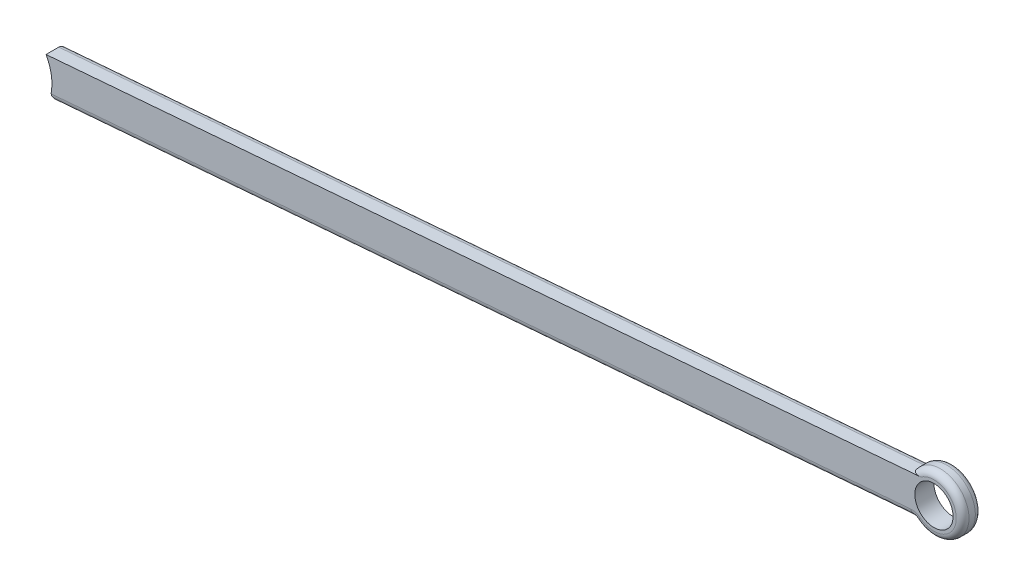
SolidWorks part; units mm, degrees
ref_plane "Front Plane" through (0, 0, 0) normal (0, 0, 1) x (1, 0, 0)
ref_plane "Top Plane" through (0, 0, 0) normal (0, 1, 0) x (1, 0, 0)
ref_plane "Right Plane" through (0, 0, 0) normal (1, 0, 0) x (0, 0, -1)
sketch "Sketch1" plane through (0, 0, 0) normal (0, 0, 1) x (1, 0, 0)
  line L0 (0, 0) -> (0, 28420.5788) construction
  line L1 (0, 0) -> (-28420.5788, 0) construction
  line L2 (-23, 10) -> (-28, 10)
  line L3 (-23, 0) -> (23, 0)
  line L4 (-23, 0) -> (-23, 10)
  line L5 (-23, 10) -> (23, 10)
  line L6 (23, 0) -> (23, 10)
  line L7 (-28, 10) -> (-41.8608, 50.4677)
  line L8 (-24.6313, 80.3256) -> (15.2446, 88.1625)
  line L9 (23, 10) -> (28, 10)
  line L10 (28, 10) -> (39.4051, 19.57)
  line L11 (39.4051, 19.57) -> (39.4051, 38.57)
  line L12 (39.4051, 38.57) -> (22.9346, 83.8223)
  line L13 (-20.22, 57.88) -> (7.2073, 203.3164) construction
  line L14 (16.5541, 81.5) -> (43.9813, 226.9364) construction
  line L15 (-27.5657, 229.7942) -> (7.2073, 203.3164) construction
  line L16 (7.2073, 203.3164) -> (43.9813, 226.9364) construction
  line L17 (43.9813, 226.9364) -> (-27.5657, 229.7942) construction
  line L18 (-27.5657, 229.7942) -> (-187.2585, 219.8842) construction
  line L19 (-152.8522, 195.7967) -> (61.1478, 205.8505) construction
  line L20 (-187.2585, 219.8842) -> (-152.8522, 195.7967) construction
  line L21 (-152.8522, 195.7967) -> (-207.7687, 192.7672) construction
  line L22 (-207.7687, 192.7672) -> (-187.2585, 219.8842) construction
  line L23 (-20.22, 57.88) -> (32.9338, 48.3578)
  line L24 (32.9338, 48.3578) -> (61.1478, 205.8505)
  circle A0 centre (-20.22, 57.88) radius 22.875 construction
  circle A1 centre (16.5541, 81.5) radius 6.79 construction
  arc A2 (-41.8608, 50.4677) -> (-24.6313, 80.3256) centre (-20.22, 57.88) cw
  arc A3 (15.2446, 88.1625) -> (22.9346, 83.8223) centre (16.5541, 81.5) cw
  circle A4 centre (-20.22, 57.88) radius 17.5 construction
  circle A5 centre (16.5541, 81.5) radius 7.5 construction
  circle A6 centre (7.2073, 203.3164) radius 13.1881 construction
  circle A7 centre (43.9813, 226.9364) radius 8.7345 construction
  circle A8 centre (-27.5657, 229.7942) radius 8.7345 construction
  circle A9 centre (-187.2585, 219.8842) radius 8.1525 construction
  circle A10 centre (-152.8522, 195.7967) radius 9.1166 construction
  dimension "D7" = 45.75
  dimension "D8" = 13.58
  dimension "D14" = 35
  dimension "D15" = 15
  dimension "D1" = 46
  dimension "D2" = 10
  dimension "D3" = 57.88
  dimension "D4" = 20.22
  dimension "D5" = 16.5541
  dimension "D6" = 81.5
  dimension "D9" = 5
  dimension "D10" = 5
  dimension "D11" = 140
  dimension "D12" = 19
  dimension "D13" = 160
  dimension "D16" = 148
  dimension "D17" = 110
  dimension "D18" = 160
  dimension "D19" = 54
  dimension "D20" = 214
  dimension "D21" = 42
  dimension "D22" = 34
  dimension "D23" = 55
  dimension "D24" = 54
  dimension "D25" = 160
sketch "Sketch3" plane through (0, 0, 0) normal (0, 0, 1) x (1, 0, 0)
  line L0 (-27.5657, 229.7942) -> (-187.2585, 219.8842) construction
  line L1 (-27.5657, 229.7942) -> (-187.2585, 219.8842) construction
  line L2 (-187.2585, 219.8842) -> (-27.5657, 229.7942) construction
  line L3 (-187.4443, 222.8784) -> (-27.7515, 232.7884)
  line L4 (-187.0727, 216.8899) -> (-27.3799, 226.7999)
  line L5 (-189.5569, 289.0107) -> (-44.042, 300.9023) construction
  line L6 (-186.4583, 292.2739) -> (-47.6293, 303.6192)
  line L7 (-185.9696, 286.2939) -> (-47.1406, 297.6391)
  arc A0 (-184.0967, 223.0861) -> (-183.725, 217.0977) centre (-187.2585, 219.8842) ccw
  arc A1 (-30.7276, 226.5922) -> (-31.0992, 232.5807) centre (-27.5657, 229.7942) ccw
  arc A2 (-187.4443, 222.8784) -> (-187.0727, 216.8899) centre (-187.2585, 219.8842) ccw
  arc A3 (-27.3799, 226.7999) -> (-27.7515, 232.7884) centre (-27.5657, 229.7942) ccw
  circle A4 centre (-27.5657, 229.7942) radius 3
  circle A5 centre (-187.2585, 219.8842) radius 3
  arc A6 (-182.6679, 290.7354) -> (-188.9785, 281.9326) centre (-189.5569, 289.0107) ccw
  arc A7 (-43.7977, 297.9123) -> (-47.0247, 300.5801) centre (-44.042, 300.9023) ccw
  arc A8 (-47.1406, 297.6391) -> (-47.6293, 303.6192) centre (-44.042, 300.9023) ccw
  arc A9 (-186.4583, 292.2739) -> (-185.9696, 286.2939) centre (-189.5569, 289.0107) ccw
  circle A10 centre (-189.5569, 289.0107) radius 7.1017
  circle A11 centre (-44.042, 300.9023) radius 3
  point P4 (-107.4121, 224.8392)
  point P17 (-116.7995, 294.9565)
  dimension "D1" = 9
  dimension "D2" = 9
  dimension "D6" = 3
  dimension "D7" = 9
  dimension "D8" = 9
  dimension "D3" = 6
  dimension "D4" = 160
  dimension "D5" = 136
sketch "Sketch2" plane through (0, 0, 0) normal (0, 0, 1) x (1, 0, 0)
  line L0 (-152.8522, 195.7967) -> (61.1478, 205.8505) construction
  line L1 (-152.8522, 195.7967) -> (61.1478, 205.8505) construction
  circle A0 centre (7.2073, 203.3164) radius 20
  circle A1 centre (7.2073, 203.3164) radius 10
  circle A2 centre (61.1478, 205.8505) radius 6
  circle A3 centre (-152.8522, 195.7967) radius 9
  arc A4 (-154.4656, 204.6509) -> (6.1924, 223.2906) centre (69.6216, -1025.099) cw
  arc A5 (-152.2126, 186.8195) -> (4.9312, 183.4463) centre (-91.8039, -661.0312) cw
  arc A6 (14.4893, 221.9436) -> (61.4538, 211.8427) centre (69.1045, 361.6475) ccw
  arc A7 (18.7678, 186.996) -> (60.9964, 199.8525) centre (59.2297, 129.8748) cw
  arc A8 (-152.8522, 195.7967) -> (7.2073, 203.3164) centre (-35.9399, -585.5045) cw construction
  circle A9 centre (-24.5427, 204.4133) radius 1.75
  circle A10 centre (-127.8522, 199.1306) radius 1.75
  circle A11 centre (-152.8522, 195.7967) radius 1.75
  circle A12 centre (61.1478, 205.8505) radius 1.75
  circle A13 centre (7.2073, 203.3164) radius 1.75
  point P2 (7.2073, 203.3164)
  dimension "D1" = 40
  dimension "D2" = 20
  dimension "D3" = 12
  dimension "D4" = 18
  dimension "D5" = 1250
  dimension "D6" = 850
  dimension "D7" = 150
  dimension "D8" = 70
  dimension "D9" = 790
  dimension "D12" = 3.5
  dimension "D13" = 3.5
  dimension "D10" = 31.75
  dimension "D11" = 25
extrude "Boss-Extrude1" add sketch "Sketch3" along normal blind 3 contours L6 A9 L7 A8 A11 A7 A10 A6
fillet "Fillet1" radius 1 7 edges at (-39.557, 301.2689, 3) (-39.557, 301.2689, 0) (-115.0189, 292.092, 3) (-47.1406, 297.6391, 1.5) (-115.0189, 292.092, 0) (-115.5076, 298.0721, 0) (-182.8971, 286.545, 1.5)
